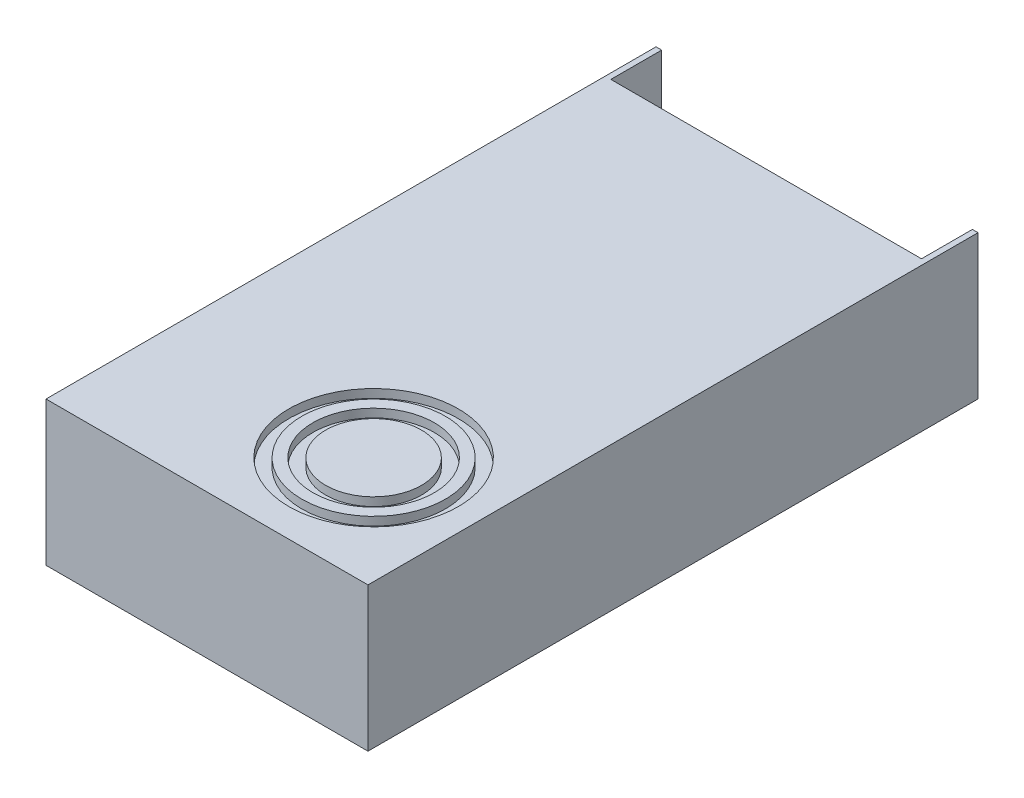
SolidWorks part; units mm, degrees
ref_plane "Спереди" through (0, 0, 0) normal (0, 0, 1) x (1, 0, 0)
ref_plane "Сверху" through (0, 0, 0) normal (0, 1, 0) x (1, 0, 0)
ref_plane "Справа" through (0, 0, 0) normal (1, 0, 0) x (0, 0, -1)
sketch "Эскиз2" plane through (0, 0, 0) normal (0, 1, 0) x (1, 0, 0)
  line L1 (-11.405, 45.4857) -> (102.595, 45.4857)
  line L2 (-11.405, 45.4857) -> (-11.405, -170.5143)
  line L3 (-11.405, -170.5143) -> (102.595, -170.5143)
  line L4 (102.595, 45.4857) -> (102.595, -170.5143)
  dimension "D1" = 114
  dimension "D2" = 216
extrude "Бобышка-Вытянуть2" add sketch "Эскиз2" along normal blind 51
sketch "Эскиз3" plane through (0, 0, 0) normal (0, -1, 0) x (1, 0, 0)
  line L0 (-11.405, 170.5143) -> (102.595, 170.5143) construction
  line L1 (-1.905, 160.5143) -> (93.095, 160.5143) construction
  line L2 (-1.905, 160.5143) -> (-1.905, -16.4857) construction
  line L3 (-1.905, -16.4857) -> (93.095, -16.4857) construction
  line L4 (93.095, 160.5143) -> (93.095, -16.4857) construction
  line L5 (45.595, 170.5143) -> (45.595, -45.4857) construction
  line L6 (102.595, -45.4857) -> (-11.405, -45.4857) construction
  line L10 (20.595, 137.5143) -> (70.595, 137.5143) construction
  line L11 (20.595, 137.5143) -> (20.595, -12.4857) construction
  line L12 (20.595, -12.4857) -> (70.595, -12.4857) construction
  line L13 (70.595, 137.5143) -> (70.595, -12.4857) construction
  circle A0 centre (-1.905, 160.5143) radius 1.5
  circle A1 centre (93.095, 160.5143) radius 1.5
  circle A2 centre (-1.905, -16.4857) radius 1.5
  circle A3 centre (93.095, -16.4857) radius 1.5
  circle A4 centre (20.595, 137.5143) radius 2
  circle A5 centre (70.595, 137.5143) radius 2
  circle A6 centre (20.595, -12.4857) radius 2
  circle A7 centre (70.595, -12.4857) radius 2
  dimension "D5" = 3
  dimension "D6" = 3
  dimension "D7" = 3
  dimension "D8" = 3
  dimension "D13" = 4
  dimension "D14" = 4
  dimension "D15" = 4
  dimension "D16" = 4
  dimension "D1" = 95
  dimension "D2" = 177
  dimension "D3" = 10
  dimension "D4" = 47.5
  dimension "D9" = 150
  dimension "D10" = 50
  dimension "D11" = 25
  dimension "D12" = 33
extrude "Вырез-Вытянуть1" cut sketch "Эскиз3" against normal blind 10
sketch "Эскиз4" plane through (0, 51, 0) normal (0, 1, 0) x (1, 0, 0)
  line L0 (102.595, 45.4857) -> (-11.405, 45.4857) construction
  line L1 (-9.405, 45.4857) -> (100.595, 45.4857)
  line L2 (-9.405, 45.4857) -> (-9.405, 27.4857)
  line L3 (-9.405, 27.4857) -> (100.595, 27.4857)
  line L4 (100.595, 45.4857) -> (100.595, 27.4857)
  line L5 (102.595, -170.5143) -> (102.595, 45.4857) construction
  line L6 (-11.405, 45.4857) -> (-11.405, -170.5143) construction
  dimension "D1" = 2
  dimension "D2" = 2
  dimension "D3" = 18
extrude "Вырез-Вытянуть2" cut sketch "Эскиз4" against normal blind 42
sketch "Эскиз5" plane through (0, 9, 0) normal (0, 1, 0) x (1, 0, 0)
  line L0 (-9.405, 27.4857) -> (100.595, 27.4857) construction
  line L1 (-7.6193, 27.4857) -> (79.3807, 27.4857)
  line L2 (-7.6193, 27.4857) -> (-7.6193, 43.4857)
  line L3 (-7.6193, 43.4857) -> (79.3807, 43.4857)
  line L4 (79.3807, 27.4857) -> (79.3807, 43.4857)
  dimension "D1" = 87
  dimension "D2" = 16
extrude "Бобышка-Вытянуть3" add sketch "Эскиз5" along normal blind 17
sketch "Эскиз6" plane through (0, 51, 0) normal (0, 1, 0) x (1, 0, 0)
  line L0 (102.595, -170.5143) -> (102.595, 45.4857) construction
  line L1 (-11.405, -170.5143) -> (102.595, -170.5143) construction
  circle A0 centre (64.595, -130.5143) radius 30
  circle A1 centre (64.595, -130.5143) radius 25.4364
  dimension "D1" = 60
  dimension "D2" = 38
  dimension "D3" = 40
extrude "Вырез-Вытянуть4" cut sketch "Эскиз6" against normal blind 3
sketch "Эскиз7" plane through (0, 51, 0) normal (0, 1, 0) x (1, 0, 0)
  circle A0 centre (64.595, -130.5143) radius 21.4937
  circle A1 centre (64.595, -130.5143) radius 16.969
extrude "Вырез-Вытянуть5" cut sketch "Эскиз7" against normal blind 3
